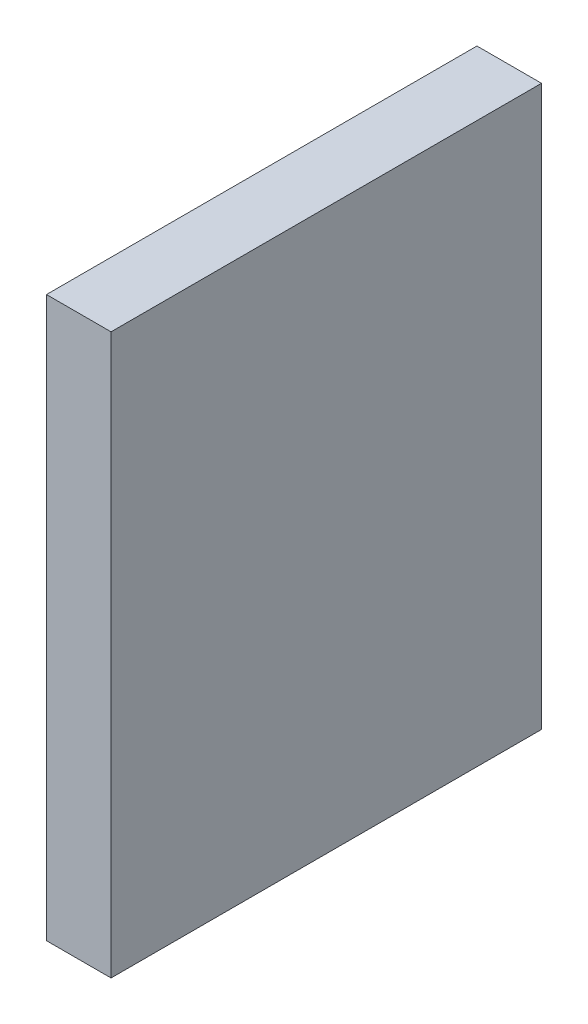
SolidWorks part; units mm, degrees
material "Balsa"
ref_plane "Plan de face" through (0, 0, 0) normal (0, 0, 1) x (1, 0, 0)
ref_plane "Plan de dessus" through (0, 0, 0) normal (0, 1, 0) x (1, 0, 0)
ref_plane "Plan de droite" through (0, 0, 0) normal (1, 0, 0) x (0, 0, -1)
sketch "Esquisse1" plane through (0, 0, 0) normal (0, 1, 0) x (1, 0, 0)
  line L1 (-54.4573, 87.1653) -> (-39.4573, 87.1653)
  line L2 (-54.4573, 87.1653) -> (-54.4573, -12.8347)
  line L3 (-54.4573, -12.8347) -> (-39.4573, -12.8347)
  line L4 (-39.4573, 87.1653) -> (-39.4573, -12.8347)
  dimension "D1" = 100
  dimension "D2" = 15
extrude "Boss.-Extru.1" add sketch "Esquisse1" along normal blind 130
